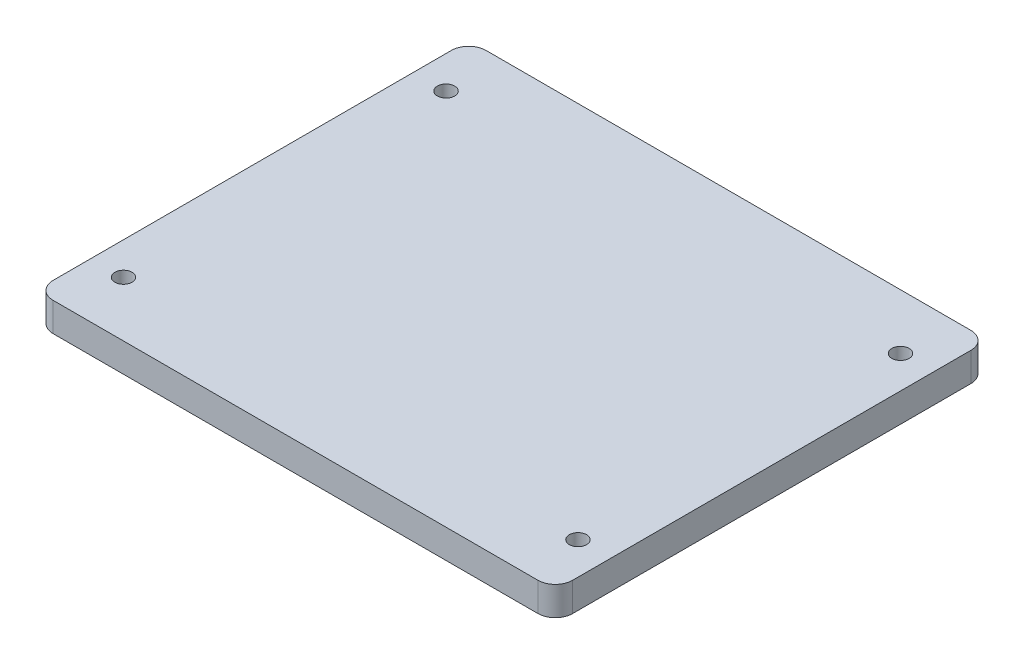
SolidWorks part; units mm, degrees
ref_plane "Front Plane" through (0, 0, 0) normal (0, 0, 1) x (1, 0, 0)
ref_plane "Top Plane" through (0, 0, 0) normal (0, 1, 0) x (1, 0, 0)
ref_plane "Right Plane" through (0, 0, 0) normal (1, 0, 0) x (0, 0, -1)
sketch "Sketch1" plane through (0, 0, 0) normal (0, 1, 0) x (1, 0, 0)
  line L1 (-45, 37.5) -> (45, 37.5)
  line L2 (-45, 37.5) -> (-45, -37.5)
  line L3 (-45, -37.5) -> (45, -37.5)
  line L4 (45, 37.5) -> (45, -37.5)
  line L5 (-45, 37.5) -> (45, -37.5) construction
  line L6 (-45, -37.5) -> (45, 37.5) construction
  point P0 (0, 0)
  dimension "D1" = 90
  dimension "D2" = 75
extrude "Boss-Extrude1" add sketch "Sketch1" along normal blind 5
sketch "Sketch2" plane through (0, 5, 0) normal (0, 1, 0) x (1, 0, 0)
  line L1 (-42.25, 31) -> (42.25, 31)
  line L2 (-42.25, 31) -> (-42.25, -31)
  line L3 (-42.25, -31) -> (42.25, -31)
  line L4 (42.25, 31) -> (42.25, -31)
  line L5 (-42.25, 31) -> (42.25, -31) construction
  line L6 (-42.25, -31) -> (42.25, 31) construction
  circle A0 centre (-39.37, 27.94) radius 1.5
  circle A1 centre (39.37, 27.94) radius 1.5
  circle A2 centre (39.37, -27.94) radius 1.5
  circle A3 centre (-39.37, -27.94) radius 1.5
  point P0 (0, 0)
  dimension "D3" = 3
  dimension "D1" = 84.5
  dimension "D2" = 62
  dimension "D4" = 3.06
  dimension "D5" = 2.88
  dimension "D6" = 2.88
  dimension "D7" = 3.06
extrude "Cut-Extrude1" cut sketch "Sketch2" against normal up to surface (5 mm away) contours A0 | A1 | A2 | A3 up to face at (0, 0, 0)
sketch "Sketch3" plane through (0, 0, 0) normal (0, -1, 0) x (1, 0, 0)
  line L0 (0, -2.75) -> (0, 2.75) construction
  line L1 (-82.5, 37.5) -> (82.5, 37.5)
  line L2 (-82.5, 37.5) -> (-82.5, -37.5)
  line L3 (-82.5, -37.5) -> (82.5, -37.5)
  line L4 (82.5, 37.5) -> (82.5, -37.5)
  line L5 (-82.5, 37.5) -> (82.5, -37.5) construction
  line L6 (-82.5, -37.5) -> (82.5, 37.5) construction
  circle A0 centre (22.5, 32.5) radius 4.5
  circle A1 centre (22.5, -32.5) radius 4.5
  circle A2 centre (-22.5, -32.5) radius 4.5
  circle A3 centre (-22.5, 32.5) radius 4.5
  point P0 (0, 0)
  dimension "D3" = 9
  dimension "D1" = 165
  dimension "D2" = 75
  dimension "D4" = 60
  dimension "D5" = 5
  dimension "D6" = 5
extrude "Cut-Extrude2" cut sketch "Sketch3" against normal blind 2 contours A2 | A3 | A0 | A1
fillet "Fillet1" radius 3 4 edges at (-45, 2.5, -37.5) (45, 2.5, -37.5) (45, 2.5, 37.5) (-45, 2.5, 37.5)
